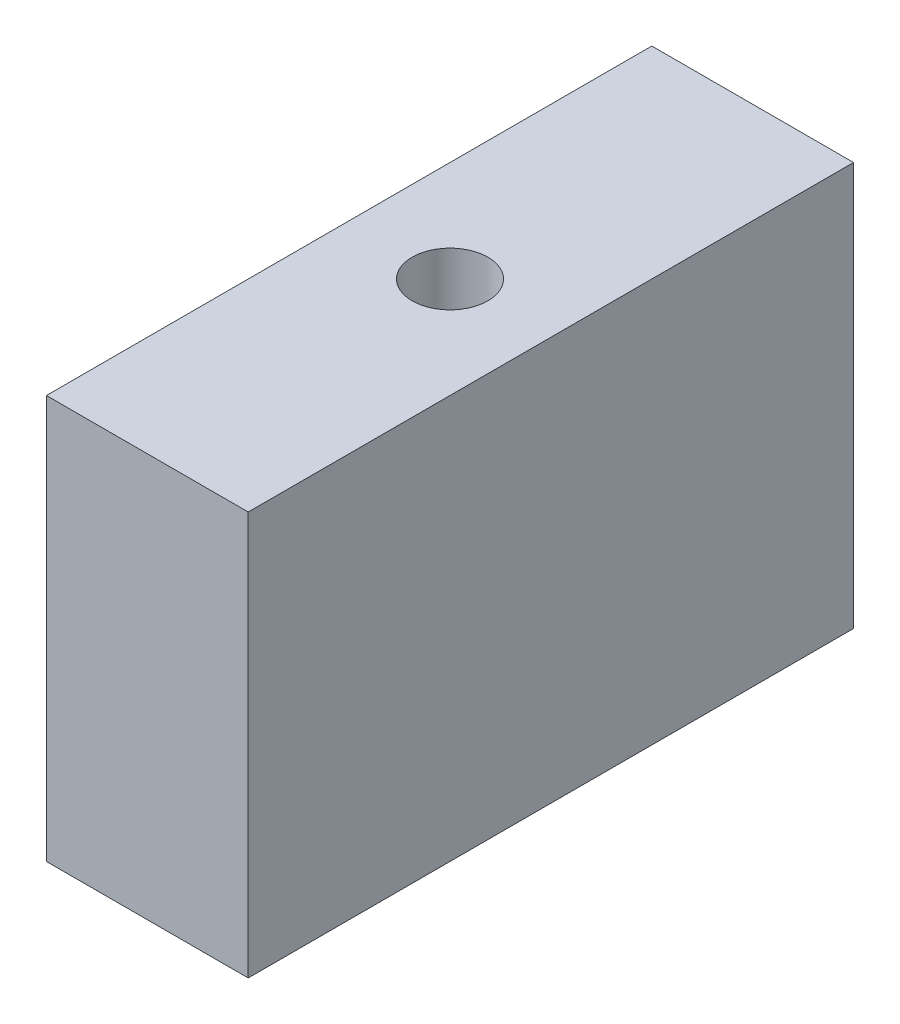
SolidWorks part; units mm, degrees
material "6061 Alloy"
ref_plane "Front Plane" through (0, 0, 0) normal (0, 0, 1) x (1, 0, 0)
ref_plane "Top Plane" through (0, 0, 0) normal (0, 1, 0) x (1, 0, 0)
ref_plane "Right Plane" through (0, 0, 0) normal (1, 0, 0) x (0, 0, -1)
sketch "Sketch1" plane through (0, 0, 0) normal (0, 1, 0) x (1, 0, 0)
  line L1 (-1.5875, -4.7625) -> (1.5875, -4.7625)
  line L2 (-1.5875, -4.7625) -> (-1.5875, 4.7625)
  line L3 (-1.5875, 4.7625) -> (1.5875, 4.7625)
  line L4 (1.5875, -4.7625) -> (1.5875, 4.7625)
  line L5 (-1.5875, -4.7625) -> (1.5875, 4.7625) construction
  line L6 (-1.5875, 4.7625) -> (1.5875, -4.7625) construction
  dimension "D1" = 3.175
  dimension "D2" = 1.5875
  dimension "D3" = 9.525
  dimension "D4" = 4.7625
extrude "Boss-Extrude1" add sketch "Sketch1" along normal blind 6.35
hole_wizard "#0-80 Tapped Hole1" positions "Sketch2" profile "Sketch3" tap size "#0-80" standard "ANSI Inch" end condition through all
sketch "Sketch2" plane through (0, 6.35, 0) normal (0, 1, 0) x (1, 0, 0)
  point P0 (0, 0)
sketch "Sketch3" plane through (0, 6.35, 0) normal (1, 0, 0) x (0, 0, 1)
  line L0 (0, 0) -> (0, 6.35)
  line L1 (0, 6.35) -> (0.5956, 6.35)
  line L2 (0.5956, 6.35) -> (0.5956, 0)
  line L5 (0.5956, 0) -> (0, 0)
  line L11 (0, -6.35) -> (0, 107.95) construction
  dimension "Thru Tap Drill Dia." = 1.1913
  dimension "Thru Tap Drill Depth" = 6.35
cosmetic thread "Hole Thread1" parameters "D2"=1.524
